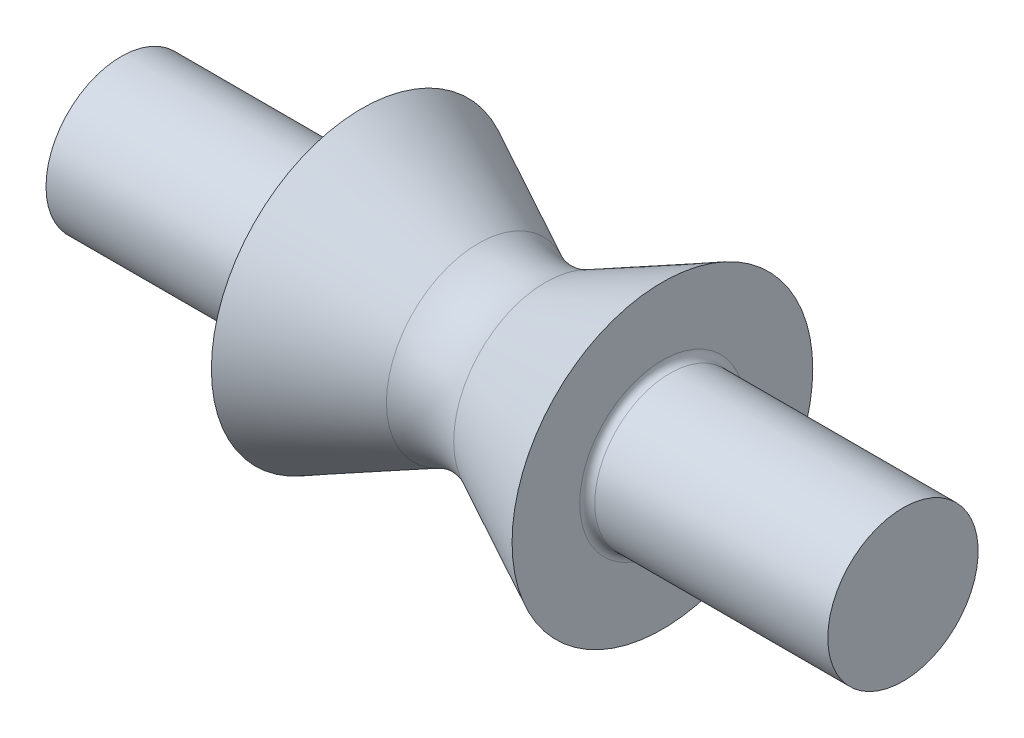
SolidWorks part; units mm, degrees
material "POLYURETHANE (11671)"
ref_plane "Front Plane" through (0, 0, 0) normal (0, 0, 1) x (1, 0, 0)
ref_plane "Top Plane" through (0, 0, 0) normal (0, 1, 0) x (1, 0, 0)
ref_plane "Right Plane" through (0, 0, 0) normal (1, 0, 0) x (0, 0, -1)
sketch "Sketch1" plane through (0, 0, 0) normal (0, 0, 1) x (1, 0, 0)
  line L0 (0, 0) -> (125.1045, 0) construction
  line L1 (0, 0) -> (0, 10)
  line L2 (0, 10) -> (32, 10)
  line L3 (32, 10) -> (32, 20)
  line L4 (32, 20) -> (52, 10)
  line L5 (52, 10) -> (72, 20)
  line L6 (72, 20) -> (72, 10)
  line L7 (72, 10) -> (104, 10)
  line L8 (104, 10) -> (104, 0)
  line L9 (0, 0) -> (104, 0)
  dimension "D1" = 10
  dimension "D2" = 10
  dimension "D3" = 10
  dimension "D4" = 10
  dimension "D5" = 32
  dimension "D6" = 32
  dimension "D7" = 20
  dimension "D8" = 20
  dimension "D9" = 10
  dimension "D10" = 22.3607
revolve "Revolve1" add sketch "Sketch1" angle 360 about L0
fillet "Fillet1" radius 1 2 edges at (72, 0, 10) (32, 0, 10)
fillet "Fillet2" radius 10 1 edges at (52, 0, 10)
